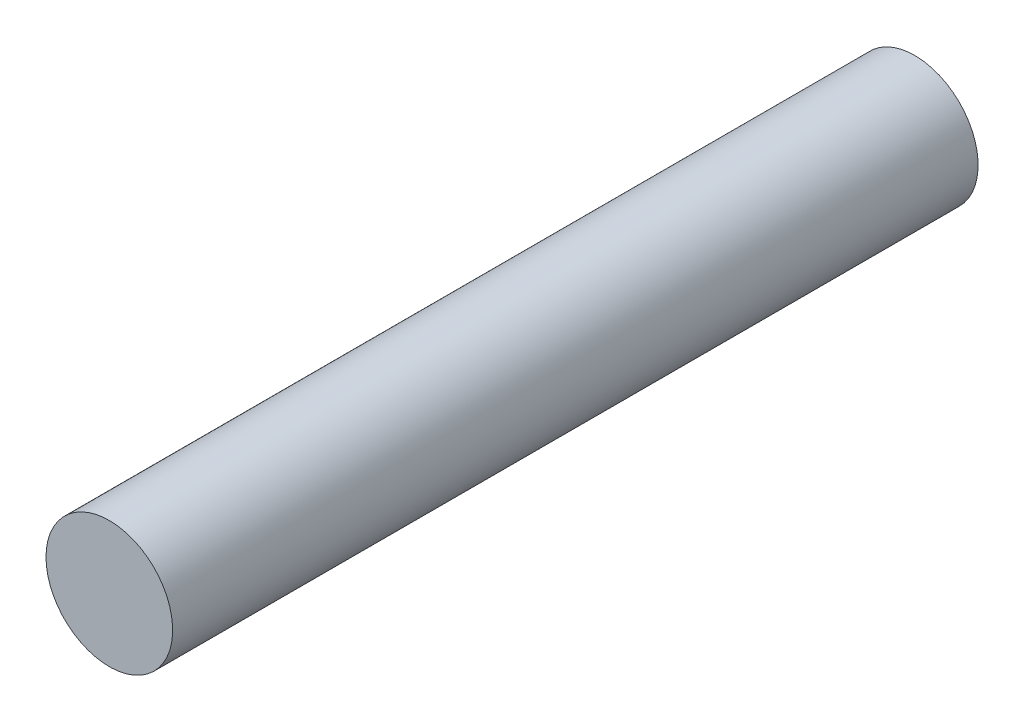
SolidWorks part; units mm, degrees
ref_plane "Plan de face" through (0, 0, 0) normal (1, 0, 0) x (0, 1, 0)
ref_plane "Plan de dessus" through (0, 0, 0) normal (0, 0, 1) x (0, 1, 0)
ref_plane "Plan de droite" through (0, 0, 0) normal (0, 1, 0) x (-1, 0, 0)
sketch "Esquisse1" plane through (0, 0, 0) normal (0, 0, 1) x (0, 1, 0)
  circle A0 centre (0, 0) radius 12.5
  dimension "D1" = 25
extrude "Boss.-Extru.2" add sketch "Esquisse1" along normal blind 159
